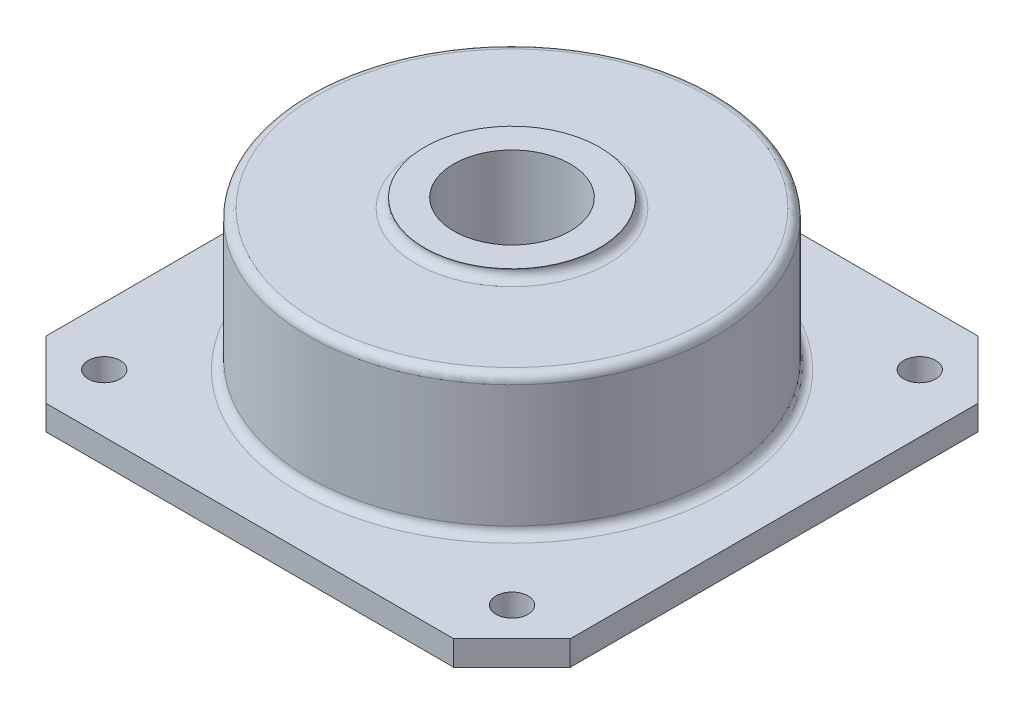
SolidWorks part; units mm, degrees
ref_plane "前视基准面" through (0, 0, 0) normal (0, 0, 1) x (1, 0, 0)
ref_plane "上视基准面" through (0, 0, 0) normal (0, 1, 0) x (1, 0, 0)
ref_plane "右视基准面" through (0, 0, 0) normal (1, 0, 0) x (0, 0, -1)
sketch "草图1" plane through (0, 0, 0) normal (0, 0, 1) x (1, 0, 0)
  line L0 (902.9735, 265.3818) -> (902.9735, 256.8818)
  line L2 (922.9735, 265.3818) -> (922.9735, 256.8818)
  line L3 (922.9735, 268.3818) -> (922.9735, 310.3818)
  line L5 (962.9735, 316.3818) -> (962.9735, 316.5818)
  line L6 (962.9735, 316.3818) -> (962.9735, 316.5818)
  line L7 (1022.9735, 316.3818) -> (1022.9735, 316.5818)
  line L8 (1022.9735, 316.3818) -> (1022.9735, 316.5818)
  line L10 (1062.9735, 265.3818) -> (1062.9735, 256.8818)
  line L11 (1062.9735, 268.3818) -> (1062.9735, 310.3818)
  line L13 (1082.9735, 265.3818) -> (1082.9735, 256.8818)
  line L14 (962.9735, 316.5818) -> (1022.9735, 316.5818)
  line L15 (1059.9735, 313.3818) -> (925.9735, 313.3818)
  line L16 (902.9735, 265.3818) -> (1082.9735, 265.3818)
  line L17 (902.9735, 256.8818) -> (1082.9735, 256.8818)
  line L18 (992.9735, 256.8818) -> (992.9735, 375.7886) construction
  arc A0 (1022.9735, 316.3818) -> (1025.9735, 313.3818) centre (1025.9735, 316.3818) ccw
  arc A1 (959.9735, 313.3818) -> (962.9735, 316.3818) centre (959.9735, 316.3818) ccw
  arc A2 (925.9735, 313.3818) -> (922.9735, 310.3818) centre (925.9735, 310.3818) ccw
  arc A3 (1062.9735, 310.3818) -> (1059.9735, 313.3818) centre (1059.9735, 310.3818) ccw
  arc A4 (919.9735, 265.3818) -> (922.9735, 268.3818) centre (919.9735, 268.3818) ccw
  arc A5 (1062.9735, 268.3818) -> (1065.9735, 265.3818) centre (1065.9735, 268.3818) ccw
revolve "旋转1" add sketch "草图1" angle 360 about L18
sketch "草图2" plane through (0, 265.3818, 0) normal (0, -1, 0) x (1, 0, 0)
  line L1 (902.9735, -90) -> (1082.9735, -90)
  line L2 (902.9735, -90) -> (902.9735, 90)
  line L3 (902.9735, 90) -> (1082.9735, 90)
  line L4 (1082.9735, -90) -> (1082.9735, 90)
  line L5 (902.9735, -90) -> (1082.9735, 90) construction
  line L6 (902.9735, 90) -> (1082.9735, -90) construction
  point P0 (992.9735, 0)
  dimension "D1" = 180
  dimension "D2" = 180
extrude "凸台-拉伸1" add sketch "草图2" along normal blind 8.5
chamfer "倒角1" distance 20 angle 45 4 edges at (902.9735, 261.1318, -90) (1082.9735, 261.1318, -90) (1082.9735, 261.1318, 90) (902.9735, 261.1318, 90)
ref_plane "基准面2" through (0, 0, 0) normal (0, 0, 1) x (1, 0, 0)
ref_plane "基准面3" through (992.9735, 0, 0) normal (-1, 0, 0) x (0, 0, 1)
sketch "草图4" plane through (0, 256.8818, 0) normal (0, -1, 0) x (1, 0, 0)
  line L0 (992.9735, 4.675) -> (992.9735, -4.675) construction
  line L1 (4.675, 0) -> (-4.675, 0) construction
  circle A0 centre (1062.9735, 70) radius 5.5
  dimension "D1" = 11
  dimension "D2" = 70
  dimension "D3" = 70
extrude "切除-拉伸1" cut sketch "草图4" against normal blind 8.5
mirror "镜向1" about plane through (0, 0, 0) normal (0, 0, 1) of "切除-拉伸1"
mirror "镜向2" about plane through (992.9735, 0, 0) normal (-1, 0, 0) of "镜向1", "切除-拉伸1"
sketch "草图5" plane through (0, 256.8818, 0) normal (0, -1, 0) x (1, 0, 0)
  line L0 (992.9735, 4.675) -> (992.9735, -4.675) construction
  line L1 (4.675, 0) -> (-4.675, 0) construction
  circle A0 centre (992.9735, 0) radius 20
  dimension "D1" = 40
extrude "切除-拉伸2" cut sketch "草图5" against normal through all
